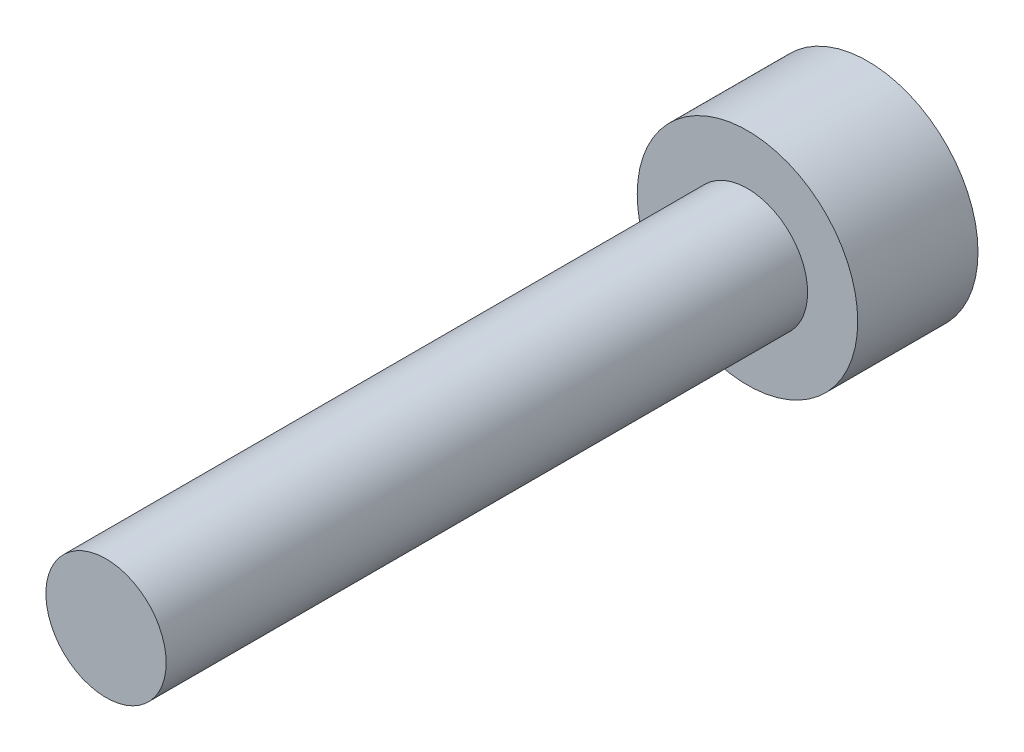
SolidWorks part; units mm, degrees
ref_plane "前视基准面" through (0, 0, 0) normal (0, 0, 1) x (1, 0, 0)
ref_plane "上视基准面" through (0, 0, 0) normal (0, 1, 0) x (1, 0, 0)
ref_plane "右视基准面" through (0, 0, 0) normal (1, 0, 0) x (0, 0, -1)
sketch "草图1" plane through (0, 0, 0) normal (0, 0, 1) x (1, 0, 0)
  circle A0 centre (0, 0) radius 1.5
  dimension "D1" = 3
extrude "金属件无牙型包络" add sketch "草图1" along normal blind 16
sketch "草图2" plane through (0, 0, 0) normal (0, 0, 1) x (1, 0, 0)
  circle A0 centre (0, 0) radius 2.75
  dimension "D1" = 5.5
extrude "标准件头部包络" add sketch "草图2" along normal blind 3 from offset 3
